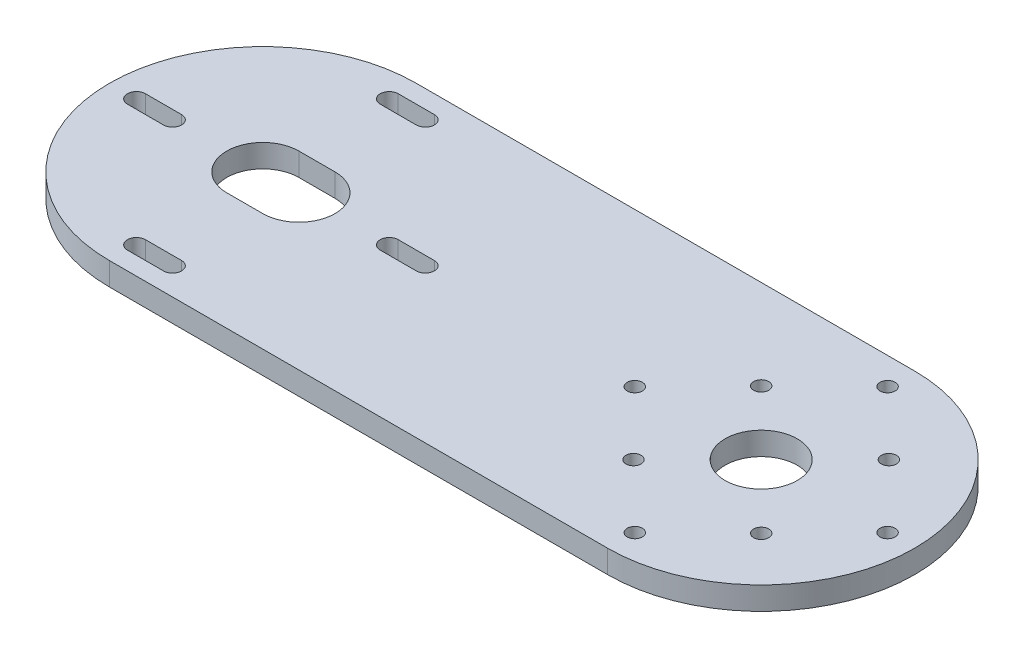
SolidWorks part; units mm, degrees
ref_plane "Front Plane" through (0, 0, 0) normal (0, 0, 1) x (1, 0, 0)
ref_plane "Top Plane" through (0, 0, 0) normal (0, 1, 0) x (1, 0, 0)
ref_plane "Right Plane" through (0, 0, 0) normal (1, 0, 0) x (0, 0, -1)
sketch "Sketch1" plane through (0, 0, 0) normal (0, 1, 0) x (1, 0, 0)
  line L0 (-138, 0) -> (0, 0) construction
  line L1 (-138, 42.5) -> (0, 42.5)
  line L6 (-138, -42.5) -> (0, -42.5)
  line L7 (-138, 35) -> (-128, 35) construction
  line L8 (-138, 37.5) -> (-128, 37.5)
  line L9 (-138, 32.5) -> (-128, 32.5)
  line L10 (-173, 0) -> (-163, 0) construction
  line L11 (-173, 2.5) -> (-163, 2.5)
  line L12 (-173, -2.5) -> (-163, -2.5)
  line L13 (-103, 0) -> (-93, 0) construction
  line L14 (-103, 2.5) -> (-93, 2.5)
  line L15 (-103, -2.5) -> (-93, -2.5)
  line L16 (-138, -35) -> (-128, -35) construction
  line L17 (-138, -32.5) -> (-128, -32.5)
  line L18 (-138, -37.5) -> (-128, -37.5)
  line L19 (17.6777, -17.6777) -> (-17.6777, 17.6777) construction
  line L20 (-138, 0) -> (-128, 0) construction
  line L21 (-17.6777, -17.6777) -> (17.6777, 17.6777) construction
  line L22 (-138, 10) -> (-128, 10)
  line L23 (-138, -10) -> (-128, -10)
  circle A1 centre (-138, 0) radius 10 construction
  circle A4 centre (-138, 0) radius 14.2875 construction
  circle A5 centre (0, 0) radius 10
  circle A8 centre (-138, 0) radius 35 construction
  circle A13 centre (-138, 0) radius 42.5
  circle A14 centre (0, 0) radius 42.5
  circle A15 centre (0, 0) radius 35 construction
  circle A16 centre (0, 35) radius 2.1
  circle A17 centre (35, 0) radius 2.1
  circle A18 centre (0, -35) radius 2.1
  circle A19 centre (-35, 0) radius 2.1
  arc A20 (-138, 37.5) -> (-138, 32.5) centre (-138, 35) ccw
  arc A21 (-128, 32.5) -> (-128, 37.5) centre (-128, 35) ccw
  arc A22 (-173, 2.5) -> (-173, -2.5) centre (-173, 0) ccw
  arc A23 (-163, -2.5) -> (-163, 2.5) centre (-163, 0) ccw
  arc A24 (-103, 2.5) -> (-103, -2.5) centre (-103, 0) ccw
  arc A25 (-93, -2.5) -> (-93, 2.5) centre (-93, 0) ccw
  arc A26 (-138, -32.5) -> (-138, -37.5) centre (-138, -35) ccw
  arc A27 (-128, -37.5) -> (-128, -32.5) centre (-128, -35) ccw
  circle A28 centre (-138, 0) radius 27.94 construction
  circle A29 centre (0, 0) radius 25 construction
  circle A30 centre (-17.6777, 17.6777) radius 2.1
  circle A31 centre (17.6777, -17.6777) radius 2.1
  circle A32 centre (-17.6777, -17.6777) radius 2.1
  circle A33 centre (17.6777, 17.6777) radius 2.1
  arc A34 (-138, 10) -> (-138, -10) centre (-138, 0) ccw
  arc A35 (-128, -10) -> (-128, 10) centre (-128, 0) ccw
  point P17 (-133, 35)
  point P22 (-168, 0)
  point P37 (-98, 0)
  point P44 (-133, -35)
  point P60 (-133, 0)
  point P66 (-133, 10)
  dimension "D2" = 20
  dimension "D4" = 4.2
  dimension "D5" = 45
  dimension "D6" = 28.575
  dimension "D7" = 20
  dimension "D9" = 55.88
  dimension "D10" = 85
  dimension "D8" = 70
  dimension "D11" = 10
  dimension "D12" = 70
  dimension "D13" = 5
  dimension "D14" = 50
  dimension "D15" = 4.2
  dimension "D16" = 10
  dimension "D3" = 138
  dimension "D17" = 20
extrude "Boss-Extrude1" add sketch "Sketch1" against normal blind 6.35
